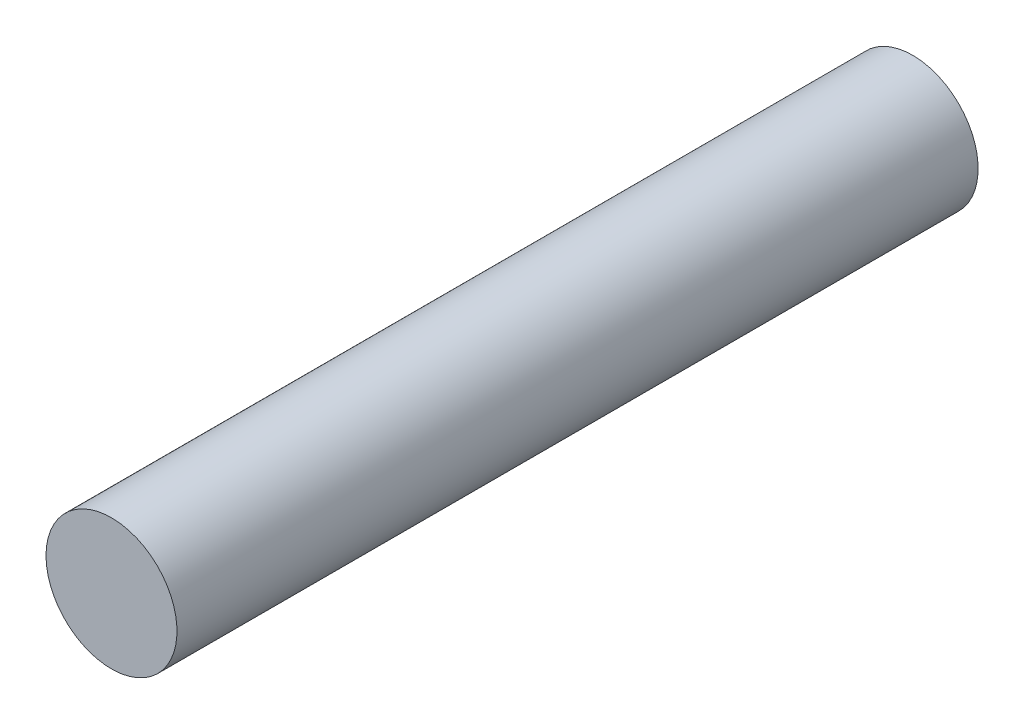
SolidWorks part; units mm, degrees
material "AISI 321 Annealed Stainless Steel (SS)"
ref_plane "Front Plane" through (0, 0, 0) normal (0, 0, 1) x (1, 0, 0)
ref_plane "Top Plane" through (0, 0, 0) normal (0, 1, 0) x (1, 0, 0)
ref_plane "Right Plane" through (0, 0, 0) normal (1, 0, 0) x (0, 0, -1)
sketch "Sketch1" plane through (0, 0, 0) normal (0, 0, 1) x (1, 0, 0)
  circle A0 centre (0, 0) radius 2.159
  dimension "D1" = 4.318
extrude "Boss-Extrude1" add sketch "Sketch1" along normal blind 26.416
